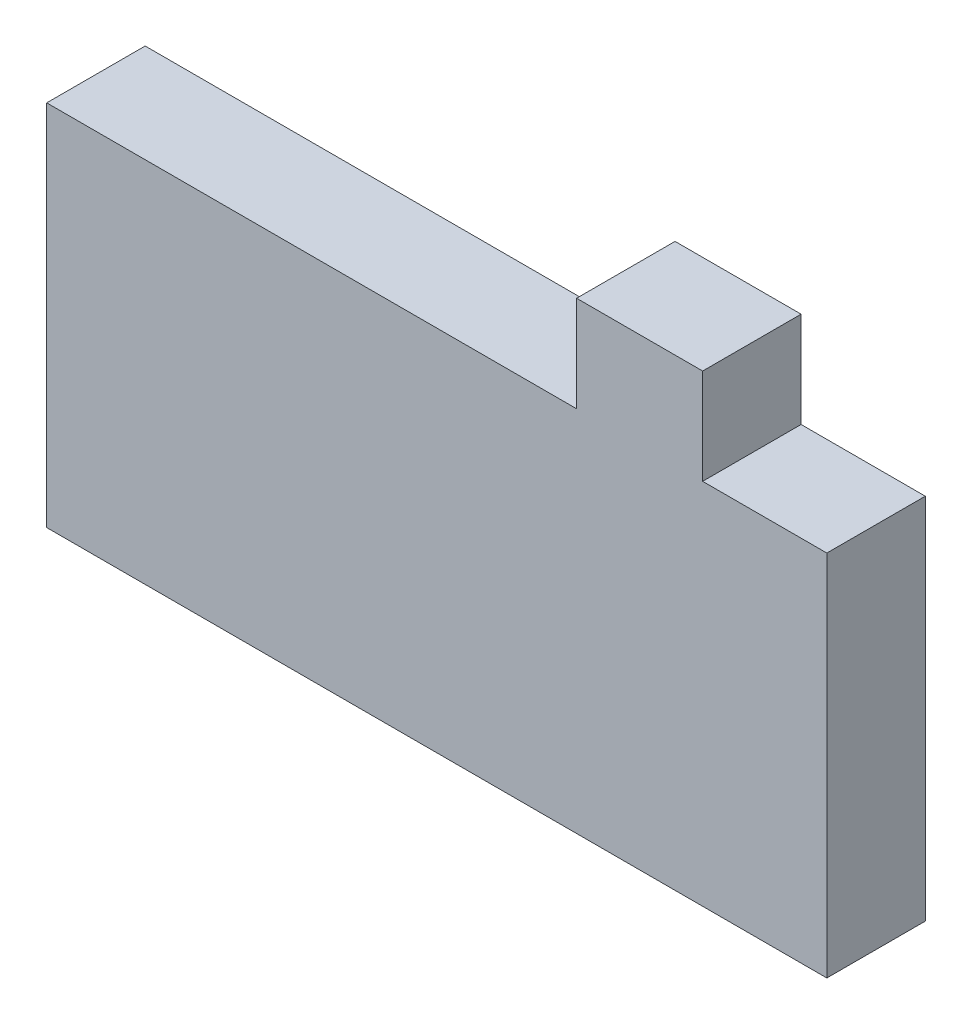
SolidWorks part; units mm, degrees
ref_plane "Front Plane" through (0, 0, 0) normal (0, 0, 1) x (1, 0, 0)
ref_plane "Top Plane" through (0, 0, 0) normal (0, 1, 0) x (1, 0, 0)
ref_plane "Right Plane" through (0, 0, 0) normal (1, 0, 0) x (0, 0, -1)
sketch "Sketch2" plane through (0, 0, 0) normal (0, 0, 1) x (1, 0, 0)
  line L0 (-61.3363, -46.981) -> (97.1314, -46.981)
  line L1 (97.1314, -46.981) -> (97.1314, 27.7785)
  line L2 (97.1314, 27.7785) -> (71.9043, 27.7785)
  line L3 (71.9043, 27.7785) -> (71.9043, 47.185)
  line L4 (71.9043, 47.185) -> (46.2999, 47.185)
  line L5 (46.2999, 47.185) -> (46.2999, 27.74)
  line L6 (46.2999, 27.74) -> (-61.3363, 27.74)
  line L7 (-61.3363, 27.74) -> (-61.3363, -46.981)
extrude "Boss-Extrude1" add sketch "Sketch2" along normal blind 20
shell "Shell1" thickness 5
